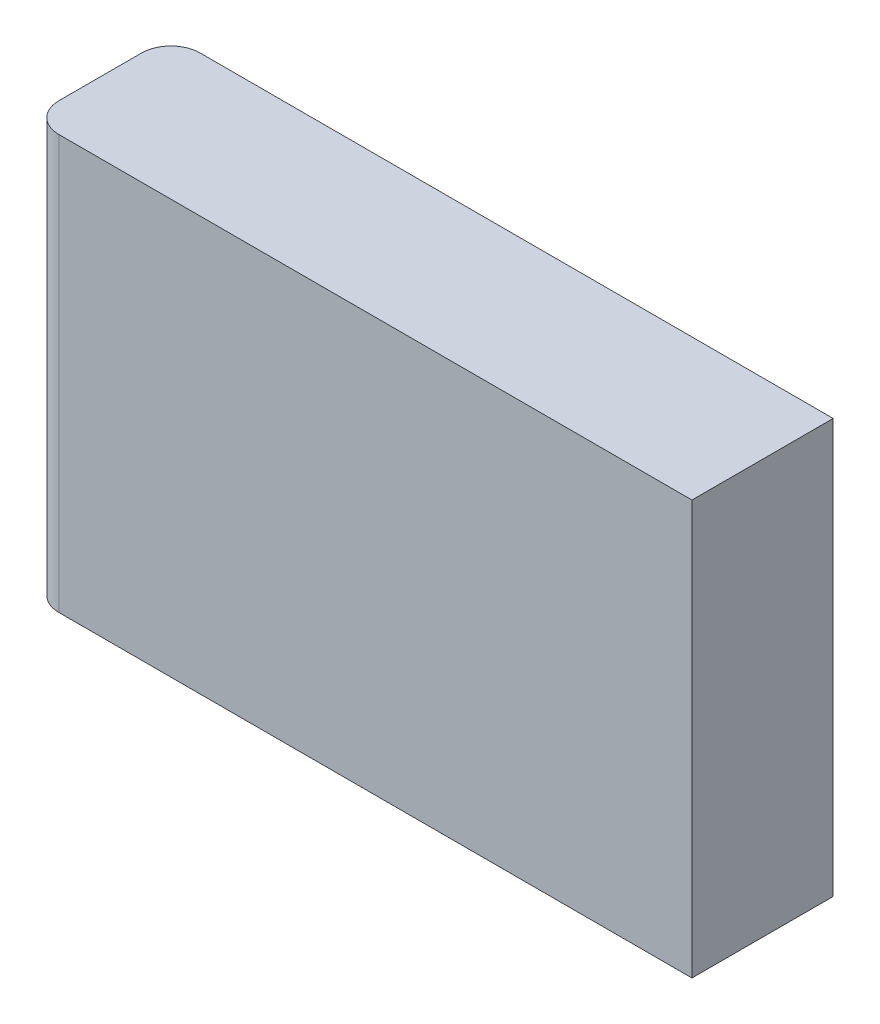
SolidWorks part; units mm, degrees
ref_plane "前视基准面" through (0, 0, 0) normal (0, 0, 1) x (1, 0, 0)
ref_plane "上视基准面" through (0, 0, 0) normal (0, 1, 0) x (1, 0, 0)
ref_plane "右视基准面" through (0, 0, 0) normal (1, 0, 0) x (0, 0, -1)
sketch "Sketch1" plane through (0, 0, 0) normal (0, 0, 1) x (1, 0, 0)
  line L1 (68, -42.5) -> (-68, -42.5)
  line L2 (68, -42.5) -> (68, 42.5)
  line L3 (68, 42.5) -> (-68, 42.5)
  line L4 (-68, -42.5) -> (-68, 42.5)
  line L5 (68, -42.5) -> (-68, 42.5) construction
  line L6 (68, 42.5) -> (-68, -42.5) construction
  point P0 (0, 0)
  dimension "D1" = 136
  dimension "D2" = 85
extrude "Boss-Extrude1" add sketch "Sketch1" along normal blind 29
fillet "Fillet1" radius 6 2 edges at (-68, 0, 0) (-68, 0, 29)
sketch "Sketch2" plane through (0, 0, 29) normal (0, 0, 1) x (1, 0, 0)
  text T0 "TATTU serie - 4S 6600mAh \r\n14.8V 4S2P 35C" font "汉仪长仿宋体" height 10
